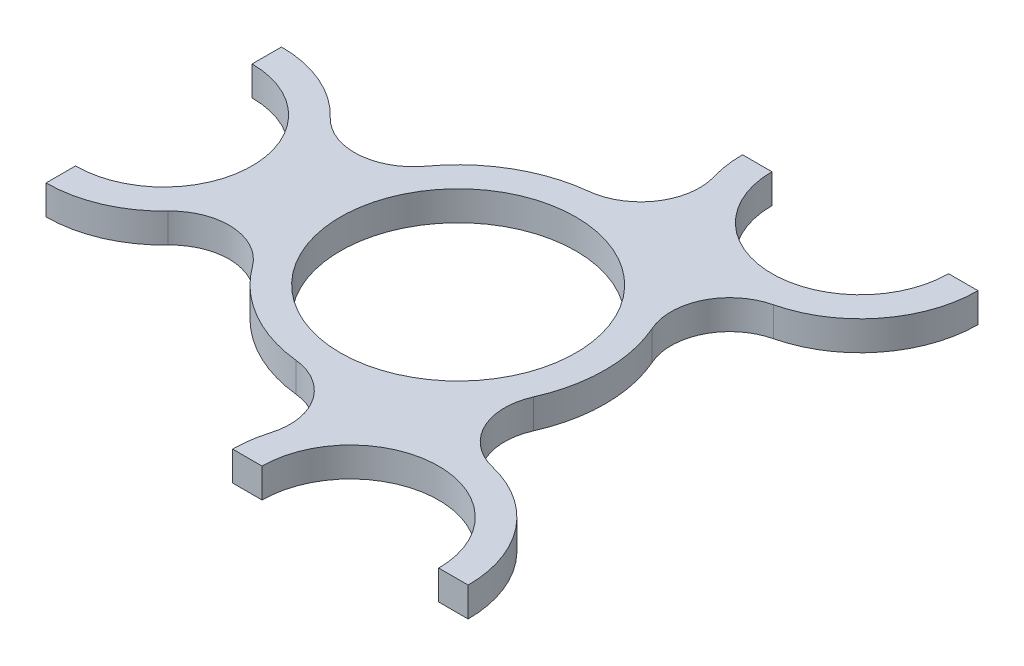
SolidWorks part; units mm, degrees
ref_plane "Front Plane" through (0, 0, 0) normal (0, 0, 1) x (1, 0, 0)
ref_plane "Top Plane" through (0, 0, 0) normal (0, 1, 0) x (1, 0, 0)
ref_plane "Right Plane" through (0, 0, 0) normal (1, 0, 0) x (0, 0, -1)
sketch "Sketch1" plane through (0, 0, 0) normal (0, 1, 0) x (1, 0, 0)
  line L0 (0, 0) -> (0, 60023.2864) construction
  line L1 (0, 0) -> (60023.2864, 0) construction
  line L2 (-100, 0) -> (-100, 50000) construction
  line L3 (50, 53.5149) -> (50, -49946.4851) construction
  line L4 (-100, 30) -> (-100, 40)
  line L5 (-100, -30) -> (-100, -40)
  line L7 (10, -86.6) -> (20, -86.6)
  line L9 (10, 86.6) -> (20, 86.6)
  line L10 (80, 86.6) -> (90, 86.6)
  line L11 (80, -86.6) -> (90, -86.6)
  arc A0 (-40.3571, -29.5178) -> (-5.3851, -49.7092) centre (0, 0) ccw
  circle A1 centre (0, 0) radius 40
  arc A2 (-100, -40) -> (-71, -27.55) centre (-100, 0) ccw
  arc A3 (-100, -30) -> (-100, 30) centre (-100, 0) ccw
  arc A5 (20, 86.6) -> (80, 86.6) centre (50, 86.6) ccw
  arc A6 (59.3596, 47.7104) -> (90, 86.6) centre (50, 86.6) ccw
  arc A7 (10, -86.6) -> (11.6406, -75.2619) centre (50, -86.6) cw
  arc A8 (20, -86.6) -> (80, -86.6) centre (50, -86.6) cw
  arc A9 (-71, 27.55) -> (-40.3571, 29.5178) centre (-56.5, 41.3249) ccw
  arc A10 (-40.3571, -29.5178) -> (-71, -27.55) centre (-56.5, -41.3249) ccw
  arc A11 (45.7425, 20.1898) -> (59.3596, 47.7104) centre (64.0395, 28.2657) cw
  arc A12 (-5.3851, 49.7092) -> (11.6406, 75.2619) centre (-7.5392, 69.5928) ccw
  arc A13 (-5.3851, -49.7092) -> (11.6406, -75.2619) centre (-7.5392, -69.5928) cw
  arc A14 (45.7425, -20.1898) -> (59.3596, -47.7104) centre (64.0395, -28.2657) ccw
  arc A15 (-71, 27.55) -> (-100, 40) centre (-100, 0) ccw
  arc A16 (45.7425, -20.1898) -> (45.7425, 20.1898) centre (0, 0) ccw
  arc A17 (-5.3851, 49.7092) -> (-40.3571, 29.5178) centre (0, 0) ccw
  arc A18 (10, 86.6) -> (11.6406, 75.2619) centre (50, 86.6) ccw
  arc A19 (59.3596, -47.7104) -> (90, -86.6) centre (50, -86.6) cw
  dimension "D1" = 80
  dimension "D2" = 100
  dimension "D3" = 80
  dimension "D4" = 60
  dimension "D6" = 40
  dimension "D7" = 50
  dimension "D8" = 80
  dimension "D9" = 60
  dimension "D11" = 40
  dimension "D12" = 20
  dimension "D5" = 100
  dimension "D10" = 86.6
extrude "Boss-Extrude1" add sketch "Sketch1" along normal blind 10
